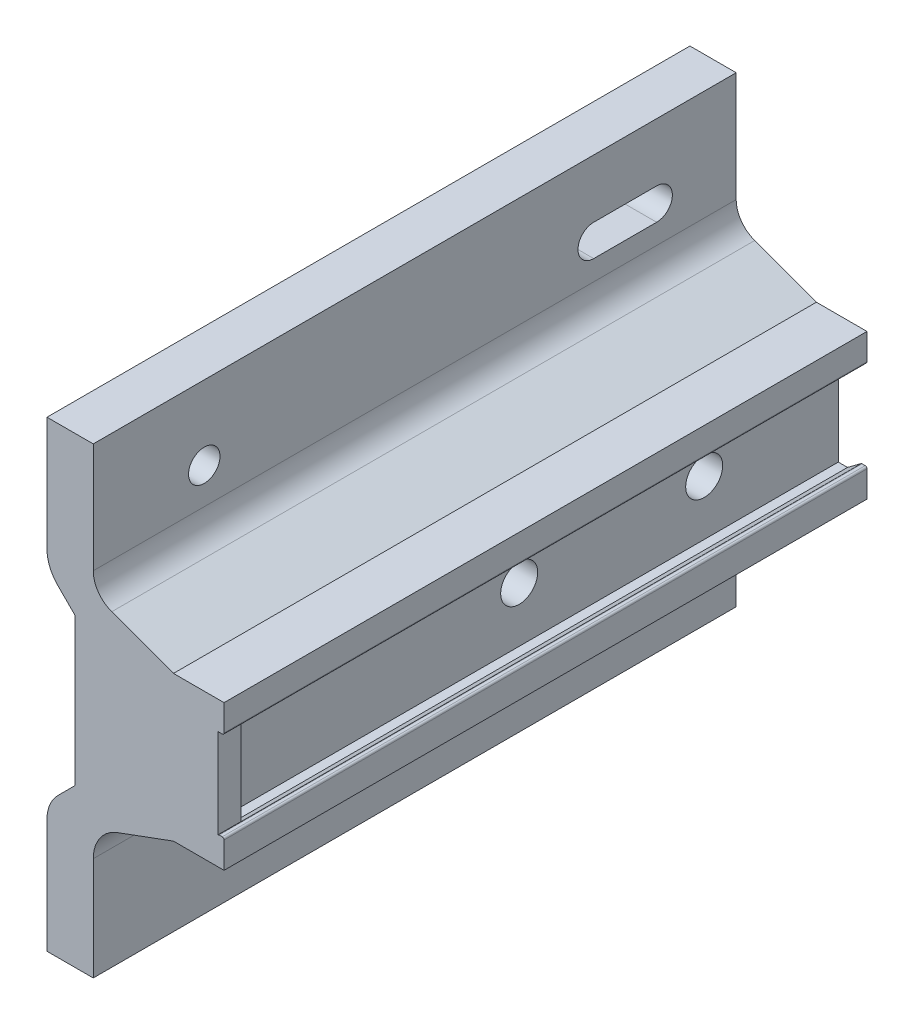
SolidWorks part; units mm, degrees
ref_plane "Front Plane" through (0, 0, 0) normal (0, 0, 1) x (1, 0, 0)
ref_plane "Top Plane" through (0, 0, 0) normal (0, 1, 0) x (1, 0, 0)
ref_plane "Right Plane" through (0, 0, 0) normal (1, 0, 0) x (0, 0, -1)
sketch "Sketch4" plane through (0, 0, 0) normal (0, 0, 1) x (1, 0, 0)
  line L1 (-4.5326, 10.3735) -> (-10.3026, 10.3735) construction
  line L2 (-6.8326, 8.1535) -> (-5.3326, 7.0335) construction
  line L3 (-7.6326, 8.1535) -> (-7.6326, -3.4065) construction
  line L4 (-6.8326, 8.1535) -> (-7.6326, 8.1535) construction
  line L5 (-13.1609, 2.3735) -> (1.8792, 2.3735) construction
  line L6 (-10.3026, 10.3735) -> (-10.3026, -5.6265) construction
  line L7 (-4.5326, 7.0335) -> (-4.5326, 10.3735) construction
  line L8 (-4.5326, -2.2865) -> (-4.5326, -5.6265) construction
  line L9 (-6.8326, -3.4065) -> (-7.6326, -3.4065) construction
  line L10 (-6.8326, -3.4065) -> (-5.3326, -2.2865) construction
  line L11 (-4.5326, -5.6265) -> (-10.3026, -5.6265) construction
  line L13 (-5.3326, 7.0335) -> (-4.5326, 7.0335) construction
  line L14 (-5.3326, -2.2865) -> (-4.5326, -2.2865) construction
  line L15 (-10.1526, 10.2235) -> (-10.1526, -5.4765)
  line L16 (-4.6826, -5.4765) -> (-10.1526, -5.4765)
  line L17 (-4.6826, -2.4365) -> (-4.6826, -5.4765)
  line L18 (-5.2828, -2.4365) -> (-4.6826, -2.4365)
  line L19 (-6.7828, -3.5565) -> (-5.2828, -2.4365)
  line L20 (-6.7828, -3.5565) -> (-7.7826, -3.5565)
  line L21 (-7.7826, 8.3035) -> (-7.7826, -3.5565)
  line L22 (-6.7828, 8.3035) -> (-7.7826, 8.3035)
  line L23 (-6.7828, 8.3035) -> (-5.2828, 7.1835)
  line L24 (-5.2828, 7.1835) -> (-4.6826, 7.1835)
  line L25 (-4.6826, 7.1835) -> (-4.6826, 10.2235)
  line L26 (-4.6826, 10.2235) -> (-10.1526, 10.2235)
  point P13 (-10.3026, 2.3735)
  point P15 (-7.6326, 2.3735)
  dimension "D1" = 1.12
  dimension "D2" = 1.5
  dimension "D3" = 1.5
  dimension "D4" = 0.8
  dimension "D5" = 5.78
  dimension "D6" = 2.3
  dimension "D7" = 16
  dimension "D8" = 1.12
  dimension "D9" = 0.15
extrude "Boss-Extrude2" add sketch "Sketch4" along normal blind 69.5
sketch "Sketch6" plane through (0, 0, 69.5) normal (0, 0, 1) x (1, 0, 0)
  line L0 (-7.6326, 2.3735) -> (-26.1204, 2.3735) construction
  line L2 (-18.8238, 27.3735) -> (-23.8238, 27.3735)
  line L3 (-23.8238, 27.3735) -> (-23.8238, 15.0303)
  line L6 (-18.8238, -22.6265) -> (-23.8238, -22.6265)
  line L7 (-18.8238, 27.3735) -> (-18.8238, 15.4978)
  line L10 (-18.8238, -22.6265) -> (-18.8238, -11.4589)
  line L11 (-22.6522, 12.2019) -> (-20.8238, 10.3735)
  line L12 (-20.8238, 10.3735) -> (-20.8238, -5.6265)
  line L13 (-20.8238, -5.6265) -> (-22.6522, -7.455)
  line L14 (-23.8238, -10.2834) -> (-23.8238, -22.6265)
  line L15 (-16.1521, -7.6859) -> (-10.1526, -5.4765)
  line L16 (-10.1526, -5.4765) -> (-10.1526, 10.2235)
  line L17 (-10.1526, 10.2235) -> (-16.82, 12.668)
  arc A1 (-16.82, 12.668) -> (-18.8238, 15.4978) centre (-15.8238, 15.4978) cw
  arc A2 (-18.8238, -11.4589) -> (-16.1521, -7.6859) centre (-14.8238, -11.4589) cw
  arc A3 (-22.6522, 12.2019) -> (-23.8238, 15.0303) centre (-19.8238, 15.0303) cw
  arc A4 (-23.8238, -10.2834) -> (-22.6522, -7.455) centre (-19.8238, -10.2834) cw
  point P16 (-10.3026, 2.3735)
  point P17 (-23.8238, 2.3735)
  point P23 (-18.8238, 13.3735)
  point P26 (-18.8238, -8.6265)
  point P31 (-23.8238, -8.6265)
  dimension "D1" = 14
  dimension "D6" = 3
  dimension "D7" = 4
  dimension "D8" = 4
  dimension "D9" = 4
  dimension "D2" = 50
  dimension "D3" = 5
  dimension "D4" = 3
  dimension "D5" = 16
extrude "Boss-Extrude3" add sketch "Sketch6" against normal up to surface (69.5 mm away) up to face at (-6.561, 2.3735, 0)
sketch "Sketch7" plane through (-7.7826, 0, 0) normal (1, 0, 0) x (0, 0, -1)
  line L0 (-69.5, 2.3735) -> (0, 2.3735) construction
  circle A0 centre (-34.5, 2.3735) radius 2
  circle A1 centre (-14.5, 2.3735) radius 2
  dimension "D1" = 4
  dimension "D2" = 4
  dimension "D3" = 35
  dimension "D4" = 55
extrude "Cut-Extrude1" cut sketch "Sketch7" against normal through all and the other way through all
sketch "Sketch8" plane through (-23.8238, 0, 0) normal (-1, 0, 0) x (0, 0, 1)
  line L0 (0, 2.3735) -> (69.5, 2.3735) construction
  line L2 (69.5, 27.3735) -> (69.5, 15.0303) construction
  line L3 (0, 27.3735) -> (69.5, 27.3735) construction
  line L4 (0, 10.3735) -> (0, -5.6265) construction
  line L5 (69.5, 10.3735) -> (69.5, -5.6265) construction
  line L6 (15.4, 21.0735) -> (8.6, 21.0735)
  line L7 (8.6, 17.6735) -> (15.4, 17.6735)
  line L8 (8.6, -12.9265) -> (15.4, -12.9265)
  line L9 (15.4, -16.3265) -> (8.6, -16.3265)
  circle A1 centre (57.5, 19.3735) radius 1.7
  circle A4 centre (57.5, -14.6265) radius 1.7
  arc A6 (15.4, 17.6735) -> (15.4, 21.0735) centre (15.4, 19.3735) ccw
  arc A7 (8.6, 21.0735) -> (8.6, 17.6735) centre (8.6, 19.3735) ccw
  arc A8 (8.6, -16.3265) -> (8.6, -12.9265) centre (8.6, -14.6265) cw
  arc A9 (15.4, -12.9265) -> (15.4, -16.3265) centre (15.4, -14.6265) cw
  dimension "D2" = 3.4
  dimension "D3" = 12
  dimension "D5" = 8
extrude "Cut-Extrude2" cut sketch "Sketch8" against normal through all and the other way through all
fillet "Fillet1" radius 0.2 4 edges at (-4.6826, 7.1835, 34.75) (-5.2828, 7.1835, 34.75) (-4.6826, -2.4365, 34.75) (-5.2828, -2.4365, 34.75)
sketch "Sketch9" plane through (0, 0, 69.5) normal (0, 0, 1) x (1, 0, 0)
  line L0 (-7.7826, 8.3035) -> (-7.7826, -3.5565)
  line L1 (-7.7826, -3.5565) -> (-6.7828, -3.5565)
  line L2 (-6.7828, -3.5565) -> (-5.336, -2.4763)
  line L3 (-5.336, -2.4763) -> (-5.336, 7.2232)
  line L4 (-5.336, 7.2232) -> (-6.7828, 8.3035)
  line L5 (-6.7828, 8.3035) -> (-7.7826, 8.3035)
extrude "Boss-Extrude4" add sketch "Sketch9" against normal blind 2.5
